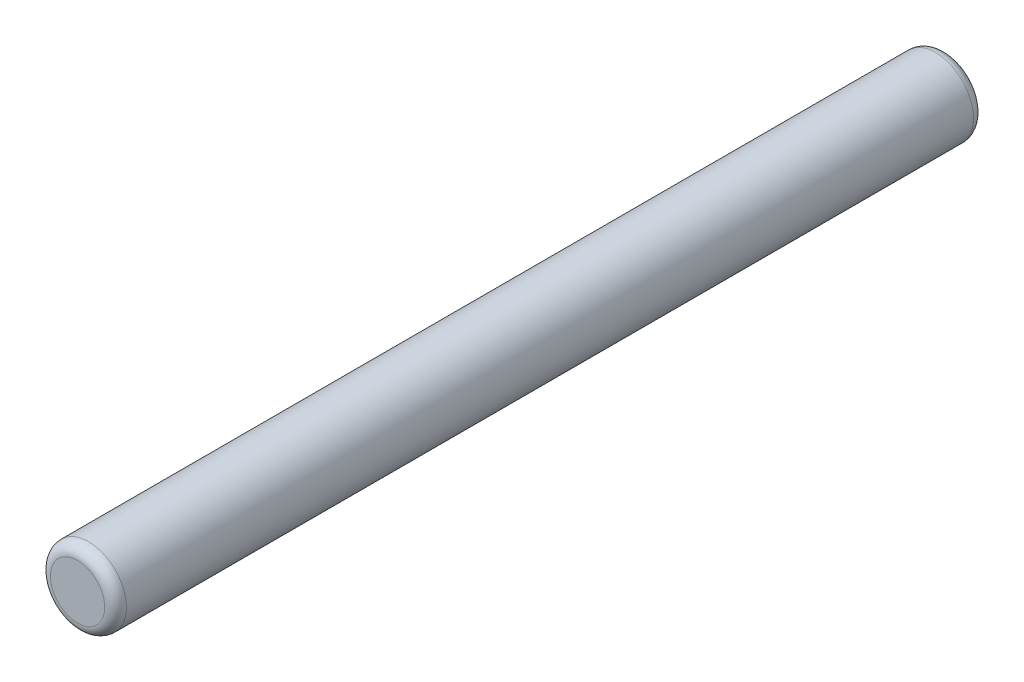
SolidWorks part; units mm, degrees
material "ABS"
ref_plane "Спереди" through (0, 0, 0) normal (0, 0, 1) x (1, 0, 0)
ref_plane "Сверху" through (0, 0, 0) normal (0, 1, 0) x (1, 0, 0)
ref_plane "Справа" through (0, 0, 0) normal (1, 0, 0) x (0, 0, -1)
sketch "Эскиз1" plane through (0, 0, 0) normal (0, 0, 1) x (1, 0, 0)
  circle A0 centre (0, 0) radius 0.875
  dimension "D1" = 1.75
extrude "Бобышка-Вытянуть1" add sketch "Эскиз1" along normal blind 20
fillet "Скругление2" radius 0.25 2 edges at (0.875, 0, 0) (0.875, 0, 20)
